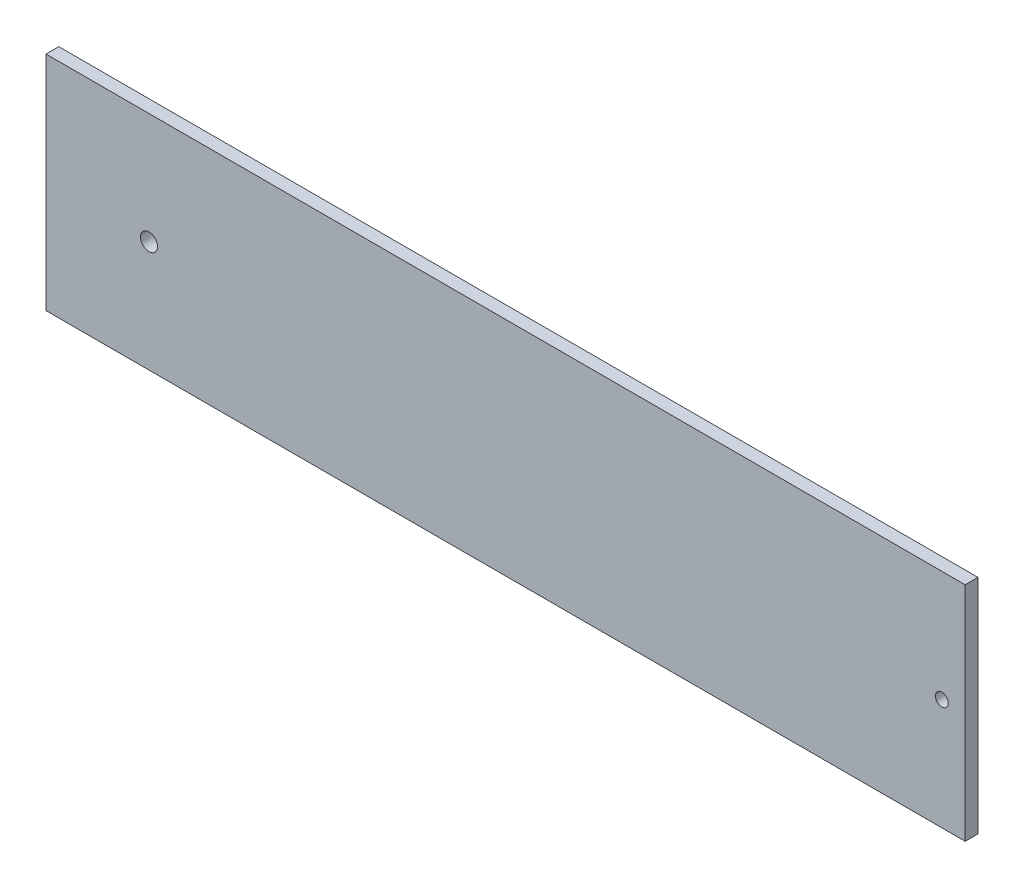
SolidWorks part; units mm, degrees
ref_plane "Front Plane" through (0, 0, 0) normal (0, 0, 1) x (1, 0, 0)
ref_plane "Top Plane" through (0, 0, 0) normal (0, 1, 0) x (1, 0, 0)
ref_plane "Right Plane" through (0, 0, 0) normal (1, 0, 0) x (0, 0, -1)
sketch "Sketch1" plane through (0, 0, 0) normal (0, 0, 1) x (1, 0, 0)
  line L1 (-120.65, -26.035) -> (120.65, -26.035)
  line L2 (-120.65, -26.035) -> (-120.65, 26.035)
  line L3 (-120.65, 26.035) -> (120.65, 26.035)
  line L4 (120.65, -26.035) -> (120.65, 26.035)
  line L5 (-120.65, -26.035) -> (120.65, 26.035) construction
  line L6 (-120.65, 26.035) -> (120.65, -26.035) construction
  point P0 (0, 0)
  dimension "D1" = 241.3
  dimension "D2" = 52.07
extrude "Boss-Extrude1" add sketch "Sketch1" along normal blind 3
sketch "Sketch2" plane through (0, 0, 3) normal (0, 0, 1) x (1, 0, 0)
  line L0 (-120.65, 26.035) -> (-120.65, -26.035) construction
  circle A0 centre (113.3394, 0) radius 2
  circle A1 centre (-96.52, 0) radius 2
  dimension "D1" = 24.13
  dimension "D2" = 4
  dimension "D3" = 4
extrude "Cut-Extrude1" cut sketch "Sketch2" against normal through all
sketch "Sketch6" plane through (0, 0, 3) normal (0, 0, 1) x (1, 0, 0)
  line L0 (100.4538, 5.9913) -> (100.4538, -6.0462)
  line L1 (120.65, 26.035) -> (120.65, -26.035)
  arc A0 (120.65, 26.035) -> (100.4538, 5.9913) centre (120.4537, 6.036) ccw
  arc A1 (100.4538, -6.0462) -> (120.65, -26.035) centre (120.4436, -6.0462) ccw
sketch "Sketch7" plane through (0, 0, 3) normal (0, 0, 1) x (1, 0, 0)
  circle A0 centre (89.2674, 0) radius 1.5
extrude "Cut-Extrude3" cut sketch "Sketch7" against normal through all
sketch "Sketch8" plane through (120.65, 0, 0) normal (1, 0, 0) x (0, 0, -1)
  line L1 (-3, 26.035) -> (0, 26.035)
  line L2 (-3, 26.035) -> (-3, -26.035)
  line L3 (-3, -26.035) -> (0, -26.035)
  line L4 (0, 26.035) -> (0, -26.035)
extrude "Cut-Extrude4" cut sketch "Sketch8" against normal blind 25.908 contours L2 L1 L4 L3
